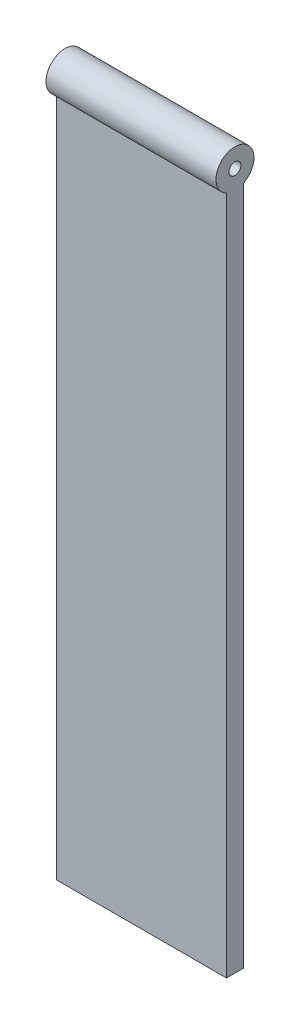
SolidWorks part; units mm, degrees
ref_plane "Front Plane" through (0, 0, 0) normal (0, 0, 1) x (1, 0, 0)
ref_plane "Top Plane" through (0, 0, 0) normal (0, 1, 0) x (1, 0, 0)
ref_plane "Right Plane" through (0, 0, 0) normal (1, 0, 0) x (0, 0, -1)
sketch "Sketch2" plane through (0, 0, 0) normal (1, 0, 0) x (0, 0, -1)
  line L0 (0, 0) -> (2, 0)
  line L1 (2, 0) -> (2, 80)
  line L2 (0, 0) -> (0, 80)
  arc A0 (2, 80) -> (0, 80) centre (1, 82) ccw
  circle A1 centre (1, 82) radius 0.7
  point P8 (1, 0)
  dimension "D4" = 1.4
  dimension "D1" = 2
  dimension "D2" = 80
  dimension "D3" = 2
extrude "Boss-Extrude1" add sketch "Sketch2" along normal blind 20
